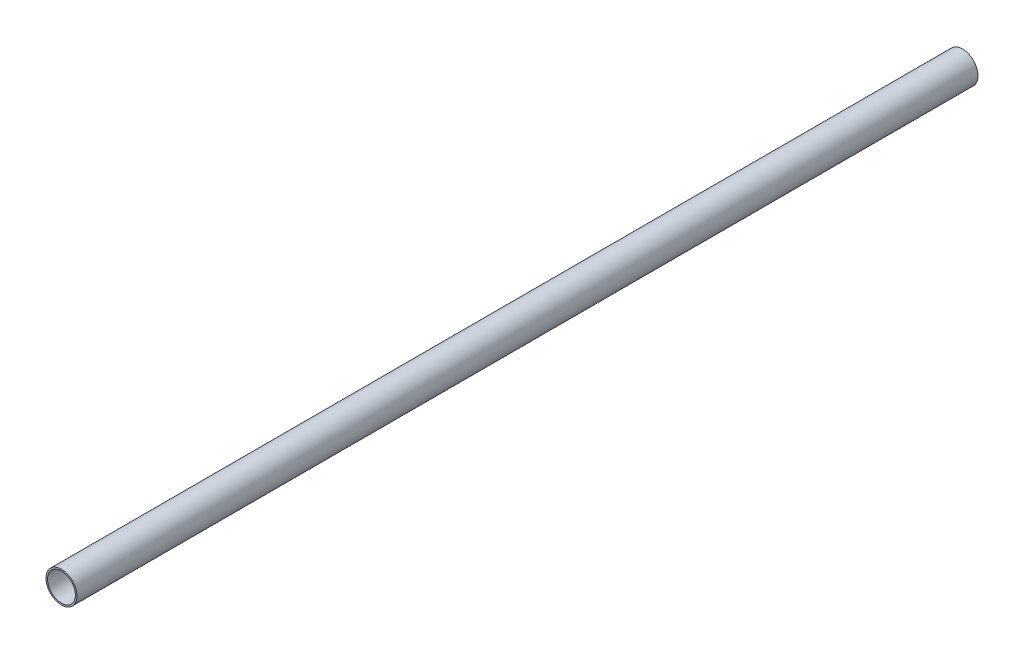
SolidWorks part; units mm, degrees
material "AISI Type A2 Tool Steel"
ref_plane "Front Plane" through (0, 0, 0) normal (0, 0, 1) x (1, 0, 0)
ref_plane "Top Plane" through (0, 0, 0) normal (0, 1, 0) x (1, 0, 0)
ref_plane "Right Plane" through (0, 0, 0) normal (1, 0, 0) x (0, 0, -1)
sketch "Sketch1" plane through (0, 0, 0) normal (0, 0, 1) x (1, 0, 0)
  circle A0 centre (0, 0) radius 5
  dimension "D1" = 10
sketch "Sketch2" plane through (0, 0, 0) normal (0, 1, 0) x (1, 0, 0)
  line L0 (0, 0) -> (0, 291)
  dimension "D1" = 291
sweep "Sweep1" add profiles "Sketch1" path "Sketch2"
shell "Shell1" thickness 0.5
